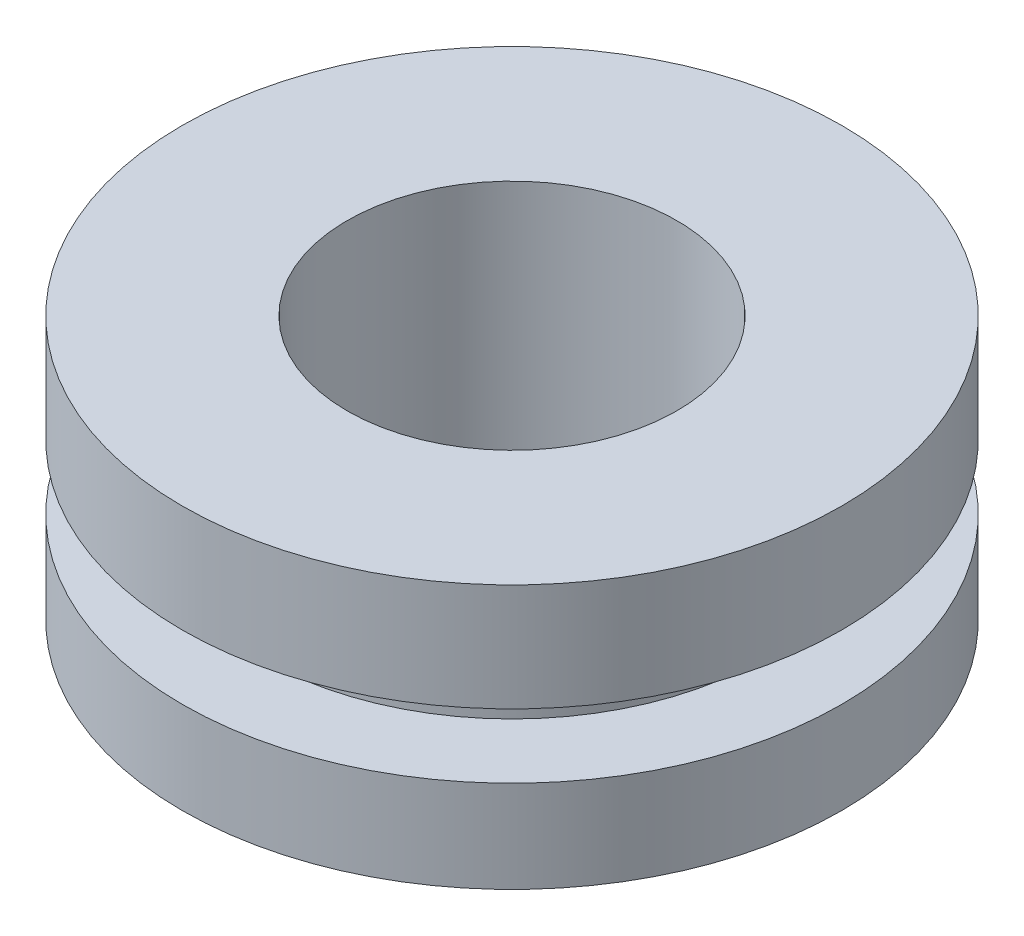
SolidWorks part; units mm, degrees
ref_plane "前视基准面" through (0, 0, 0) normal (0, 0, 1) x (1, 0, 0)
ref_plane "上视基准面" through (0, 0, 0) normal (0, 1, 0) x (1, 0, 0)
ref_plane "右视基准面" through (0, 0, 0) normal (1, 0, 0) x (0, 0, -1)
sketch "草图1" plane through (0, 0, 0) normal (0, 1, 0) x (1, 0, 0)
  circle A0 centre (0, 0) radius 2.5
  circle A1 centre (0, 0) radius 5
  dimension "D1" = 5
  dimension "D2" = 10
extrude "凸台-拉伸1" add sketch "草图1" along normal blind 4
sketch "草图2" plane through (0, 0, 0) normal (0, 0, 1) x (1, 0, 0)
  line L0 (-5, 2.3713) -> (-3.8068, 2.3713)
  line L1 (-5, 4) -> (-5, 0) construction
  line L2 (-3.8068, 2.3713) -> (-3.8068, 1.3954)
  line L3 (-3.8068, 1.3954) -> (-5, 1.3954)
  line L4 (-5, 1.3954) -> (-5, 2.3713)
ref_axis "基准轴1" through (0, 4, 0) along (0, -1, 0)
revolve "切除-旋转1" cut sketch "草图2" angle 360 about axis through (0, 4, 0) along (0, -1, 0)
